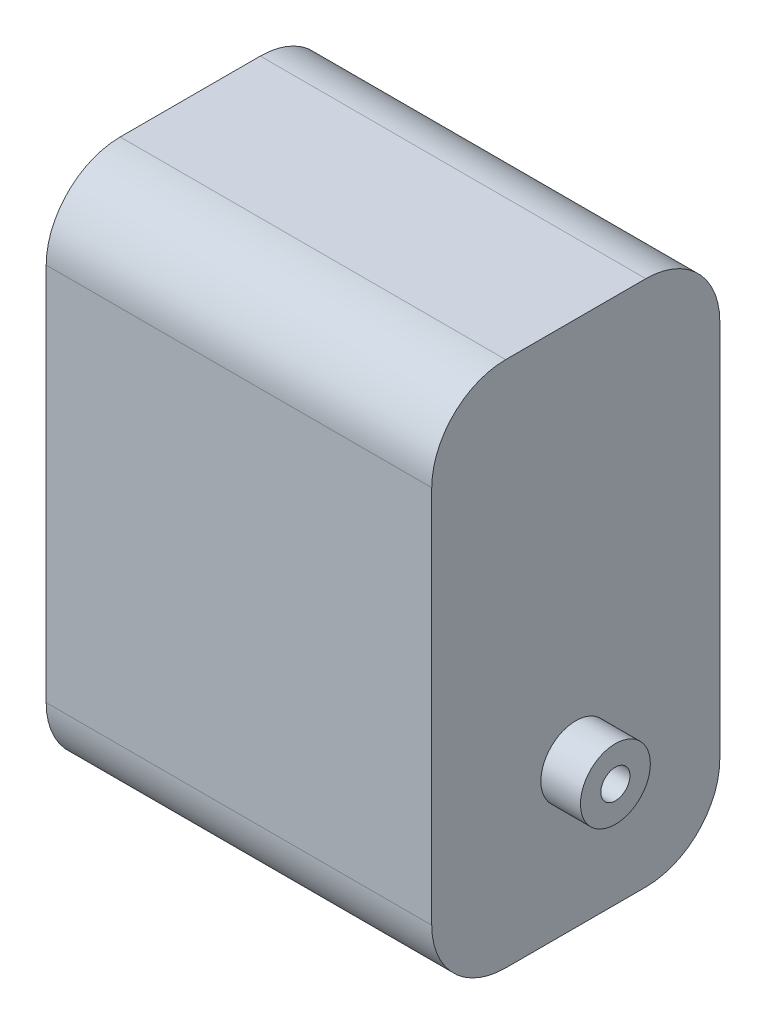
SolidWorks part; units mm, degrees
material "CMR DEFAULT - CHANGE MATERIAL"
ref_plane "XY PLANE - TOP" through (0, 0, 0) normal (0, 0, 1) x (1, 0, 0)
ref_plane "XZ PLANE - SIDE" through (0, 0, 0) normal (0, 1, 0) x (1, 0, 0)
ref_plane "YZ PLANE - FRONT" through (0, 0, 0) normal (1, 0, 0) x (0, 0, -1)
sketch "Sketch1" plane through (0, 0, 0) normal (1, 0, 0) x (0, 0, -1)
  line L1 (-12.365, -22.615) -> (12.365, -22.615)
  line L2 (-12.365, -22.615) -> (-12.365, 22.615)
  line L3 (-12.365, 22.615) -> (12.365, 22.615)
  line L4 (12.365, -22.615) -> (12.365, 22.615)
  line L5 (0, 22.615) -> (0, -22.615) construction
  line L6 (-12.365, 0) -> (12.365, 0) construction
  point P0 (0, 0)
  dimension "D1" = 24.73
  dimension "D2" = 45.23
extrude "Boss-Extrude1" add sketch "Sketch1" along normal blind 33.1
sketch "Sketch2" plane through (33.1, 0, 0) normal (1, 0, 0) x (0, 0, -1)
  line L0 (-12.365, -22.615) -> (12.365, -22.615) construction
  circle A0 centre (0, -10.245) radius 3
  circle A1 centre (0, -10.245) radius 1.25
  dimension "D1" = 6
  dimension "D2" = 2.5
  dimension "D3" = 12.37
extrude "Boss-Extrude2" add sketch "Sketch2" along normal blind 3.4
fillet "Fillet1" radius 6.35 4 edges at (16.55, 22.615, -12.365) (16.55, -22.615, -12.365) (16.55, -22.615, 12.365) (16.55, 22.615, 12.365)
